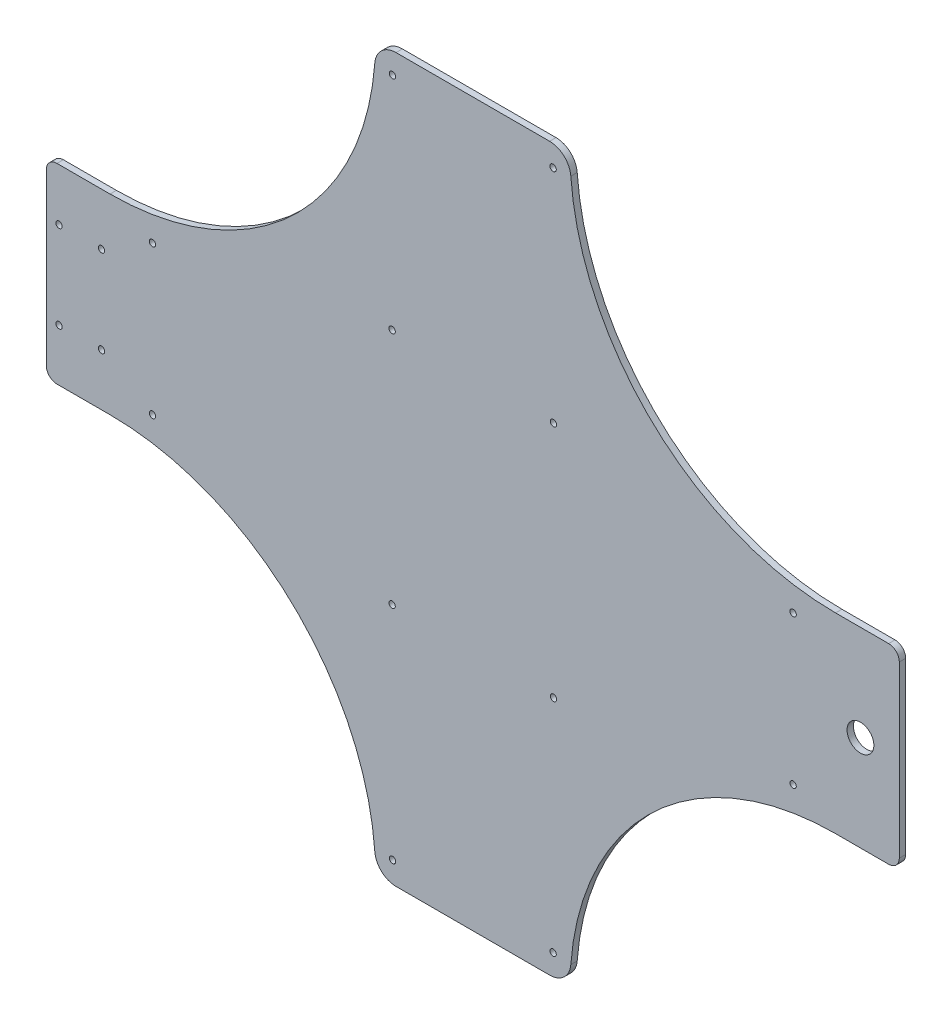
SolidWorks part; units mm, degrees
ref_plane "前视基准面" through (0, 0, 0) normal (0, 0, 1) x (1, 0, 0)
ref_plane "上视基准面" through (0, 0, 0) normal (0, 1, 0) x (1, 0, 0)
ref_plane "右视基准面" through (0, 0, 0) normal (1, 0, 0) x (0, 0, -1)
other "Configuration Table"
sketch "草图2" plane through (0, 0, 0) normal (0, 0, 1) x (1, 0, 0)
  line L1 (-16.5831, 25) -> (0, 25)
  line L5 (91.6, 25) -> (108.1831, 25)
  line L7 (0, 0) -> (-125, 0) construction
  line L9 (-125, -170) -> (358.0521, -170) construction
  line L10 (91.6, 0) -> (216.6, 0) construction
  line L19 (-16.5831, 25) -> (-96.5831, 25)
  line L20 (-96.5831, 25) -> (-96.5831, 0)
  line L21 (-96.5831, 0) -> (0, 0)
  line L22 (45.8, 0) -> (45.8, -318) construction
  line L23 (188.1831, 0) -> (91.6, 0)
  line L24 (188.1831, 25) -> (188.1831, 0)
  line L25 (108.1831, 25) -> (188.1831, 25)
  line L27 (91.6, -365) -> (108.1831, -365)
  line L28 (-16.5831, -365) -> (0, -365)
  line L30 (91.6, -340) -> (216.6, -340) construction
  line L31 (108.1831, -365) -> (188.1831, -365)
  line L32 (188.1831, -365) -> (188.1831, -340)
  line L33 (188.1831, -340) -> (91.6, -340)
  line L34 (0, -340) -> (-125, -340) construction
  line L35 (-96.5831, -340) -> (0, -340)
  line L36 (-96.5831, -365) -> (-96.5831, -340)
  line L37 (-16.5831, -365) -> (-96.5831, -365)
  line L38 (0, 0) -> (0, 25) construction
  line L39 (91.6, 0) -> (91.6, 25) construction
  line L40 (0, 25) -> (0, 55)
  line L41 (0, 55) -> (91.6, 55)
  line L42 (91.6, 55) -> (91.6, 25)
  line L43 (0, -365) -> (0, -395)
  line L44 (91.6, -395) -> (91.6, -365)
  line L45 (0, -395) -> (91.6, -395)
  line L46 (-125, -125) -> (-155, -125)
  line L47 (-155, -125) -> (-155, -215)
  line L48 (-125, -215) -> (-155, -215)
  line L50 (246.6, -215) -> (216.6, -215)
  line L51 (246.6, -125) -> (246.6, -215)
  line L52 (216.6, -125) -> (246.6, -125)
  arc A0 (0, 0) -> (-125, -125) centre (-125, 0) cw
  arc A1 (91.6, 0) -> (216.6, -125) centre (216.6, 0) ccw
  arc A2 (91.6, -340) -> (216.6, -215) centre (216.6, -340) cw
  arc A3 (0, -340) -> (-125, -215) centre (-125, -340) ccw
  point P17 (216.6, -170)
  dimension "D1" = 125
  dimension "D2" = 125
  dimension "D3" = 30
  dimension "D4" = 25
  dimension "D5" = 30
  dimension "D6" = 30
  dimension "D7" = 91.6
  dimension "D8" = 45
  dimension "D9" = 80
  dimension "D10" = 30
extrude "凸台-拉伸1" add sketch "草图2" along normal blind 3
sketch "草图4" plane through (0, 0, 3) normal (0, 0, 1) x (1, 0, 0)
  line L0 (-86.5831, 25) -> (-86.5831, 0) construction
  line L1 (0, 25) -> (-96.5831, 25) construction
  line L2 (-96.5831, 0) -> (0, 0) construction
  line L4 (-90.5831, 25) -> (-90.5831, 0) construction
  line L5 (-96.5831, 25) -> (-96.5831, 0) construction
  line L6 (0, 0) -> (91.6, 0) construction
  line L7 (0, 25) -> (-96.5831, 25) construction
  line L11 (45.8, 0) -> (45.8, -284.9604) construction
  line L13 (182.1831, 25) -> (182.1831, 0) construction
  line L14 (178.1831, 25) -> (178.1831, 0) construction
  circle A0 centre (-90.5831, 20) radius 1.5
  circle A1 centre (-90.5831, 5) radius 1.5
  circle A6 centre (-90.5831, -345) radius 1.5
  circle A7 centre (-90.5831, -360) radius 1.5
  circle A8 centre (182.1831, -360) radius 1.5
  circle A9 centre (182.1831, -345) radius 1.5
  circle A10 centre (182.1831, 5) radius 1.5
  circle A11 centre (182.1831, 20) radius 1.5
  dimension "D3" = 5
  dimension "D1" = 3
  dimension "D2" = 6
extrude "切除-拉伸2" cut sketch "草图4" against normal blind 10
sketch "草图5" plane through (0, 0, 3) normal (0, 0, 1) x (1, 0, 0)
  line L0 (0, 55) -> (0, 25) construction
  line L1 (91.6, 55) -> (0, 55) construction
  line L2 (246.6, -215) -> (246.6, -125) construction
  line L3 (246.6, -125) -> (216.6, -125) construction
  line L4 (246.6, -170) -> (186.6778, -170) construction
  line L5 (45.8, 55) -> (45.8, -58.0498) construction
  line L6 (91.6, 55) -> (0, 55) construction
  line L7 (0, -395) -> (91.6, -395) construction
  circle A0 centre (8, -10) radius 1.5
  circle A1 centre (83.6, -10) radius 1.5
  circle A2 centre (83.6, -330) radius 1.5
  circle A3 centre (8, -330) radius 1.5
  circle A4 centre (196.6, -135) radius 1.5
  circle A5 centre (196.6, -205) radius 1.5
  circle A6 centre (-105, -205) radius 1.5
  circle A7 centre (-105, -135) radius 1.5
  dimension "D1" = 3
  dimension "D4" = 3
  dimension "D2" = 65
  dimension "D3" = 8
  dimension "D5" = 50
  dimension "D6" = 10
  dimension "D7" = 65
  dimension "D8" = 65
  dimension "D9" = 65
extrude "切除-拉伸3" cut sketch "草图5" against normal blind 10
fillet "圆角1" radius 5 16 edges at (-96.5831, 0, 1.5) (-96.5831, 25, 1.5) (-155, -125, 1.5) (-155, -215, 1.5) (-96.5831, -340, 1.5) (-96.5831, -365, 1.5) (0, -395, 1.5) (91.6, -395, 1.5) (188.1831, -340, 1.5) (188.1831, -365, 1.5) (246.6, -215, 1.5) (246.6, -125, 1.5) (188.1831, 0, 1.5) (188.1831, 25, 1.5) (91.6, 55, 1.5) (0, 55, 1.5)
sketch "草图6" plane through (0, 0, 3) normal (0, 0, 1) x (1, 0, 0)
  line L1 (0, 25) -> (-116.748, 25)
  line L2 (0, 25) -> (0, 0)
  line L3 (0, 0) -> (-116.748, 0)
  line L4 (-116.748, 25) -> (-116.748, 0)
  line L5 (91.6, 25) -> (215.6736, 25)
  line L6 (91.6, 25) -> (91.6, 0)
  line L7 (91.6, 0) -> (215.6736, 0)
  line L8 (215.6736, 25) -> (215.6736, 0)
  line L9 (0, -340) -> (-98.2209, -340)
  line L10 (0, -340) -> (0, -365)
  line L11 (0, -365) -> (-98.2209, -365)
  line L12 (-98.2209, -340) -> (-98.2209, -365)
  line L13 (91.6, -340) -> (209.2343, -340)
  line L14 (91.6, -340) -> (91.6, -365)
  line L15 (91.6, -365) -> (209.2343, -365)
  line L16 (209.2343, -340) -> (209.2343, -365)
extrude "切除-拉伸4" cut sketch "草图6" against normal blind 10
sketch "草图7" plane through (0, 0, 3) normal (0, 0, 1) x (1, 0, 0)
  line L0 (86.6, 55) -> (5, 55) construction
  line L1 (78.3, 0) -> (13.3, 0)
  line L2 (78.3, 0) -> (78.3, 110)
  line L3 (78.3, 110) -> (13.3, 110)
  line L4 (13.3, 0) -> (13.3, 110)
  line L5 (78.3, 0) -> (13.3, 110) construction
  line L6 (78.3, 110) -> (13.3, 0) construction
  line L7 (-155, -170) -> (80.5438, -170) construction
  line L8 (-155, -130) -> (-155, -210) construction
  line L9 (78.3, -450) -> (13.3, -450)
  line L10 (13.3, -340) -> (13.3, -450)
  line L11 (78.3, -340) -> (13.3, -340)
  line L12 (78.3, -340) -> (78.3, -450)
  point P0 (45.8, 55)
  dimension "D1" = 65
  dimension "D2" = 110
extrude "切除-拉伸5" cut sketch "草图7" against normal blind 10
fillet "圆角2" radius 5 4 edges at (13.3, -395, 1.5) (78.3, -395, 1.5) (78.3, 55, 1.5) (13.3, 55, 1.5)
fillet "圆角3" radius 5 4 edges at (78.3, -340, 1.5) (13.3, -340, 1.5) (78.3, 0, 1.5) (13.3, 0, 1.5)
sketch "草图9" plane through (0, 0, 3) normal (0, 0, 1) x (1, 0, 0)
  line L0 (246.6, -170) -> (191.1414, -170) construction
  line L2 (246.6, -210) -> (246.6, -130) construction
  circle A1 centre (228.3087, -170) radius 6.3081
extrude "切除-拉伸7" cut sketch "草图9" against normal blind 10
sketch "草图10" plane through (0, 0, 3) normal (0, 0, 1) x (1, 0, 0)
  line L0 (-125, -125) -> (-150, -125) construction
  line L1 (-149, -149.5) -> (-129, -149.5) construction
  line L2 (-149, -149.5) -> (-149, -190.5) construction
  line L3 (-149, -190.5) -> (-129, -190.5) construction
  line L4 (-129, -149.5) -> (-129, -190.5) construction
  line L5 (-155, -130) -> (-155, -210) construction
  circle A0 centre (-149, -149.5) radius 1.5
  circle A1 centre (-129, -149.5) radius 1.5
  circle A2 centre (-149, -190.5) radius 1.5
  circle A3 centre (-129, -190.5) radius 1.5
  dimension "D5" = 3
  dimension "D6" = 3
  dimension "D7" = 3
  dimension "D8" = 3
  dimension "D1" = 41
  dimension "D2" = 20
  dimension "D3" = 24.5
  dimension "D4" = 6
extrude "切除-拉伸8" cut sketch "草图10" against normal blind 10
sketch "草图11" plane through (0, 0, 3) normal (0, 0, 1) x (1, 0, 0)
  line L5 (18.3, 0) -> (73.3, 0) construction
  line L6 (7.8, -114) -> (83.8, -114) construction
  line L7 (7.8, -114) -> (7.8, -226) construction
  line L8 (7.8, -226) -> (83.8, -226) construction
  line L9 (83.8, -114) -> (83.8, -226) construction
  line L10 (45.8, -226) -> (45.8, -114) construction
  line L11 (7.8, -170) -> (83.8, -170) construction
  line L12 (246.6, -210) -> (246.6, -130) construction
  circle A0 centre (7.8, -114) radius 1.5
  circle A1 centre (83.8, -114) radius 1.5
  circle A2 centre (83.8, -226) radius 1.5
  circle A3 centre (7.8, -226) radius 1.5
  point P0 (45.8, -170)
  dimension "D5" = 3
  dimension "D6" = 3
  dimension "D7" = 3
  dimension "D8" = 3
  dimension "D1" = 170
  dimension "D2" = 200.8
  dimension "D3" = 76
  dimension "D4" = 112
extrude "切除-拉伸9" cut sketch "草图11" against normal blind 10
sketch "草图12" plane through (0, 0, 3) normal (0, 0, 1) x (1, 0, 0)
  line L0 (0, -340) -> (0, -390) construction
  line L1 (0, 0) -> (120.5861, 0)
  line L2 (0, 0) -> (0, 63.3472)
  line L3 (0, 63.3472) -> (120.5861, 63.3472)
  line L4 (120.5861, 0) -> (120.5861, 63.3472)
  line L5 (0, -340) -> (131.7743, -340)
  line L6 (0, -340) -> (0, -406.6044)
  line L7 (0, -406.6044) -> (131.7743, -406.6044)
  line L8 (131.7743, -340) -> (131.7743, -406.6044)
  arc A0 (0, -340) -> (-125, -215) centre (-125, -340) ccw construction
extrude "切除-拉伸10" cut sketch "草图12" against normal blind 10
fillet "圆角4" radius 10 4 edges at (0, 0, 1.5) (91.6, 0, 1.5) (91.6, -340, 1.5) (0, -340, 1.5)
